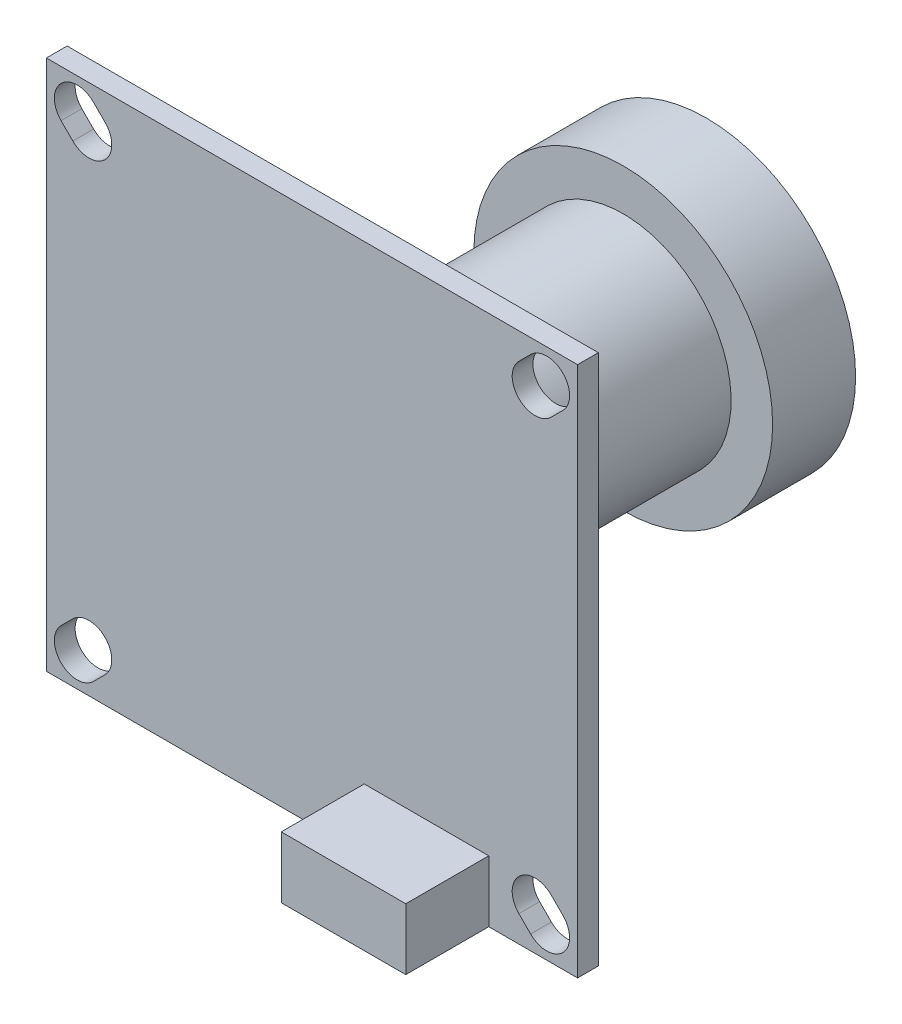
SolidWorks part; units mm, degrees
ref_plane "Plan de face" through (0, 0, 0) normal (0, 0, 1) x (1, 0, 0)
ref_plane "Plan de dessus" through (0, 0, 0) normal (0, 1, 0) x (1, 0, 0)
ref_plane "Plan de droite" through (0, 0, 0) normal (1, 0, 0) x (0, 0, -1)
sketch "Esquisse1" plane through (0, 0, 0) normal (0, 0, 1) x (1, 0, 0)
  line L0 (-14.1438, 14.1438) -> (-13.4367, 13.4367) construction
  line L1 (-16, 16) -> (16, 16)
  line L2 (-16, 16) -> (-16, -16)
  line L3 (-16, -16) -> (16, -16)
  line L4 (16, 16) -> (16, -16)
  line L5 (-13.1716, 15.1161) -> (-12.4645, 14.409)
  line L6 (-15.1161, 13.1716) -> (-14.409, 12.4645)
  line L7 (-16, 16) -> (16, -16) construction
  line L8 (14.1438, 14.1438) -> (13.4367, 13.4367) construction
  line L9 (15.1161, 13.1716) -> (14.409, 12.4645)
  line L10 (13.1716, 15.1161) -> (12.4645, 14.409)
  line L11 (14.1438, -14.1438) -> (13.4367, -13.4367) construction
  line L12 (13.1716, -15.1161) -> (12.4645, -14.409)
  line L13 (15.1161, -13.1716) -> (14.409, -12.4645)
  line L14 (-14.1438, -14.1438) -> (-13.4367, -13.4367) construction
  line L15 (-15.1161, -13.1716) -> (-14.409, -12.4645)
  line L16 (-13.1716, -15.1161) -> (-12.4645, -14.409)
  arc A0 (-13.1716, 15.1161) -> (-15.1161, 13.1716) centre (-14.1438, 14.1438) ccw
  arc A1 (-14.409, 12.4645) -> (-12.4645, 14.409) centre (-13.4367, 13.4367) ccw
  arc A2 (15.1161, 13.1716) -> (13.1716, 15.1161) centre (14.1438, 14.1438) ccw
  arc A3 (12.4645, 14.409) -> (14.409, 12.4645) centre (13.4367, 13.4367) ccw
  arc A4 (13.1716, -15.1161) -> (15.1161, -13.1716) centre (14.1438, -14.1438) ccw
  arc A5 (14.409, -12.4645) -> (12.4645, -14.409) centre (13.4367, -13.4367) ccw
  arc A6 (-15.1161, -13.1716) -> (-13.1716, -15.1161) centre (-14.1438, -14.1438) ccw
  arc A7 (-12.4645, -14.409) -> (-14.409, -12.4645) centre (-13.4367, -13.4367) ccw
  point P7 (-13.7903, 13.7903)
  point P13 (0, 0)
  point P19 (13.7903, 13.7903)
  point P26 (13.7903, -13.7903)
  point P33 (-13.7903, -13.7903)
  point P38 (0, 0)
  dimension "D3" = 1
  dimension "D1" = 32
  dimension "D2" = 2.75
  dimension "D4" = 2.625
  dimension "D6" = 2.2097
  dimension "D5" = 4
extrude "Boss.-Extru.1" add sketch "Esquisse1" along normal blind 1.25
sketch "Esquisse2" plane through (0, 0, 1.25) normal (0, 0, 1) x (1, 0, 0)
  line L0 (-16, -16) -> (16, -16) construction
  line L1 (10.65, -16) -> (3.15, -16)
  line L2 (10.65, -16) -> (10.65, -12.3)
  line L3 (10.65, -12.3) -> (3.15, -12.3)
  line L4 (3.15, -16) -> (3.15, -12.3)
  line L5 (16, -16) -> (16, 16) construction
  dimension "D1" = 5.35
  dimension "D2" = 7.5
  dimension "D3" = 3.7
extrude "Boss.-Extru.2" add sketch "Esquisse2" along normal blind 5
sketch "Esquisse3" plane through (0, 0, 0) normal (0, 0, -1) x (-1, 0, 0)
  line L0 (-6.5, 6.5) -> (6.5, 6.5)
  line L1 (6.5, 6.5) -> (6.5, 2)
  line L2 (6.5, 2) -> (8.5, 2)
  line L3 (8.5, -2) -> (6.5, -2)
  line L4 (6.5, -2) -> (6.5, -6.5)
  line L5 (6.5, -6.5) -> (-6.5, -6.5)
  line L6 (-6.5, -6.5) -> (-6.5, -2)
  line L7 (-6.5, -2) -> (-8.5, -2)
  line L8 (-8.5, 2) -> (-6.5, 2)
  line L9 (-6.5, 2) -> (-6.5, 6.5)
  line L10 (-6.5, 6.5) -> (6.5, -6.5) construction
  line L11 (-16, 16) -> (16, 16) construction
  line L12 (16, 16) -> (16, -16) construction
  arc A0 (8.5, 2) -> (8.5, -2) centre (8.5, 0) cw
  arc A1 (-8.5, -2) -> (-8.5, 2) centre (-8.5, 0) cw
  point P13 (0, 0)
  point P17 (0, 16)
  point P22 (16, 0)
  dimension "D3" = 2
  dimension "D1" = 13
  dimension "D2" = 13
  dimension "D4" = 2
extrude "Boss.-Extru.3" add sketch "Esquisse3" along normal blind 3.5
sketch "Esquisse4" plane through (0, 0, -3.5) normal (0, 0, -1) x (-1, 0, 0)
  line L0 (6.5, 6.5) -> (-6.5, 6.5) construction
  circle A0 centre (0, 0) radius 6.5
extrude "Boss.-Extru.4" add sketch "Esquisse4" along normal blind 14
sketch "Esquisse5" plane through (0, 0, -17.5) normal (0, 0, -1) x (-1, 0, 0)
  circle A0 centre (0, 0) radius 9
  dimension "D1" = 18
extrude "Boss.-Extru.5" add sketch "Esquisse5" along normal blind 5
sketch "Esquisse6" plane through (0, 0, 0) normal (1, 0, 0) x (0, 0, -1)
  line L0 (22.5, 0) -> (24.5, 0)
  line L1 (22.5, -9) -> (22.5, 9) construction
  line L2 (22.5, -9) -> (22.5, 9) construction
  line L3 (24.5, 0) -> (24.5, -1.7553) construction
  line L4 (22.5, 0) -> (22.5, 9)
  arc A0 (24.5, 0) -> (22.5, 9) centre (3.25, 0) ccw
  point P5 (22.5, 0)
  dimension "D1" = 2
revolve "Révolution2" add sketch "Esquisse6" angle 360 about L0
